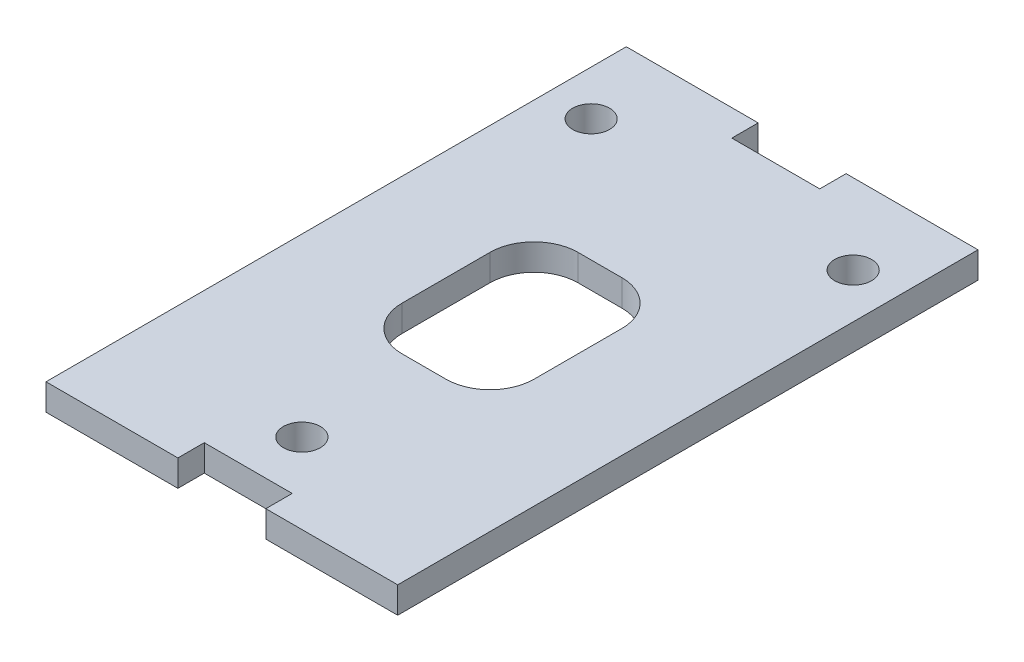
SolidWorks part; units mm, degrees
ref_plane "Front Plane" through (0, 0, 0) normal (0, 0, 1) x (1, 0, 0)
ref_plane "Top Plane" through (0, 0, 0) normal (0, 1, 0) x (1, 0, 0)
ref_plane "Right Plane" through (0, 0, 0) normal (1, 0, 0) x (0, 0, -1)
sketch "Sketch1" plane through (0, 0, 0) normal (0, 1, 0) x (1, 0, 0)
  line L0 (0, 33) -> (40, 33) construction
  line L1 (0, 0) -> (15, 0)
  line L2 (0, 0) -> (0, 3)
  line L3 (0, 3) -> (15, 3)
  line L4 (15, 0) -> (15, 3)
  line L5 (25, 0) -> (40, 0)
  line L6 (25, 0) -> (25, 3)
  line L7 (25, 3) -> (40, 3)
  line L8 (40, 0) -> (40, 3)
  line L9 (0, 3) -> (40, 3)
  line L10 (0, 3) -> (0, 63)
  line L11 (0, 63) -> (40, 63)
  line L12 (40, 3) -> (40, 63)
  line L13 (3, 59) -> (3, 7) construction
  line L14 (1.5, 60.5) -> (38.5, 60.5) construction
  line L15 (1.5, 60.5) -> (1.5, 5.5) construction
  line L16 (1.5, 5.5) -> (38.5, 5.5) construction
  line L17 (38.5, 60.5) -> (38.5, 5.5) construction
  line L18 (3, 7) -> (37, 7) construction
  line L19 (37, 59) -> (37, 7) construction
  line L20 (3, 59) -> (37, 59) construction
  line L21 (25, 63) -> (40, 63)
  line L22 (40, 66) -> (40, 63)
  line L23 (25, 66) -> (40, 66)
  line L24 (25, 66) -> (25, 63)
  line L25 (0, 63) -> (15, 63)
  line L26 (15, 66) -> (15, 63)
  line L27 (0, 66) -> (15, 66)
  line L28 (0, 66) -> (0, 63)
  line L29 (20, 63) -> (20, 3) construction
  line L30 (0, 63) -> (-3, 63)
  line L31 (0, 63) -> (0, 3)
  line L32 (0, 3) -> (-3, 3)
  line L33 (-3, 63) -> (-3, 3)
  line L34 (40, 3) -> (43, 3)
  line L35 (43, 63) -> (43, 3)
  line L36 (40, 63) -> (43, 63)
  line L37 (40, 63) -> (40, 3)
  circle A0 centre (5.1, 56.9) radius 2.1
  circle A1 centre (34.9, 56.9) radius 2.1
  circle A2 centre (20, 9.1) radius 2.1
  point P19 (1.5, 33)
  point P20 (20, 60.5)
  point P21 (20, 33)
  dimension "D8" = 4.2
  dimension "D1" = 60
  dimension "D2" = 40
  dimension "D3" = 15
  dimension "D4" = 3
  dimension "D5" = 55
  dimension "D6" = 37
  dimension "D9" = 3
  dimension "D7" = 1.5
extrude "Boss-Extrude1" add sketch "Sketch1" along normal blind 3 contours L7 L12 L11 L10 L3 L9 A2 A1 A0 | L27 L28 L11 L26 | L23 L24 L11 L22 | L5 L8 L7 L6 | L1 L4 L3 L2 | L36 L35 L34
sketch "Sketch3" plane through (0, 3, 0) normal (0, 1, 0) x (1, 0, 0)
  line L1 (12.5, 43) -> (27.5, 43)
  line L2 (12.5, 43) -> (12.5, 23)
  line L3 (12.5, 23) -> (27.5, 23)
  line L4 (27.5, 43) -> (27.5, 23)
  line L5 (0, 0) -> (0, 66) construction
  line L6 (15, 63) -> (25, 63) construction
  point P6 (0, 33)
  point P7 (12.5, 33)
  point P10 (20, 63)
  point P11 (20, 43)
  dimension "D1" = 20
  dimension "D2" = 15
extrude "Cut-Extrude1" cut sketch "Sketch3" against normal through all
fillet "Fillet1" radius 5 4 edges at (27.5, 1.5, -43) (27.5, 1.5, -23) (12.5, 1.5, -23) (12.5, 1.5, -43)
